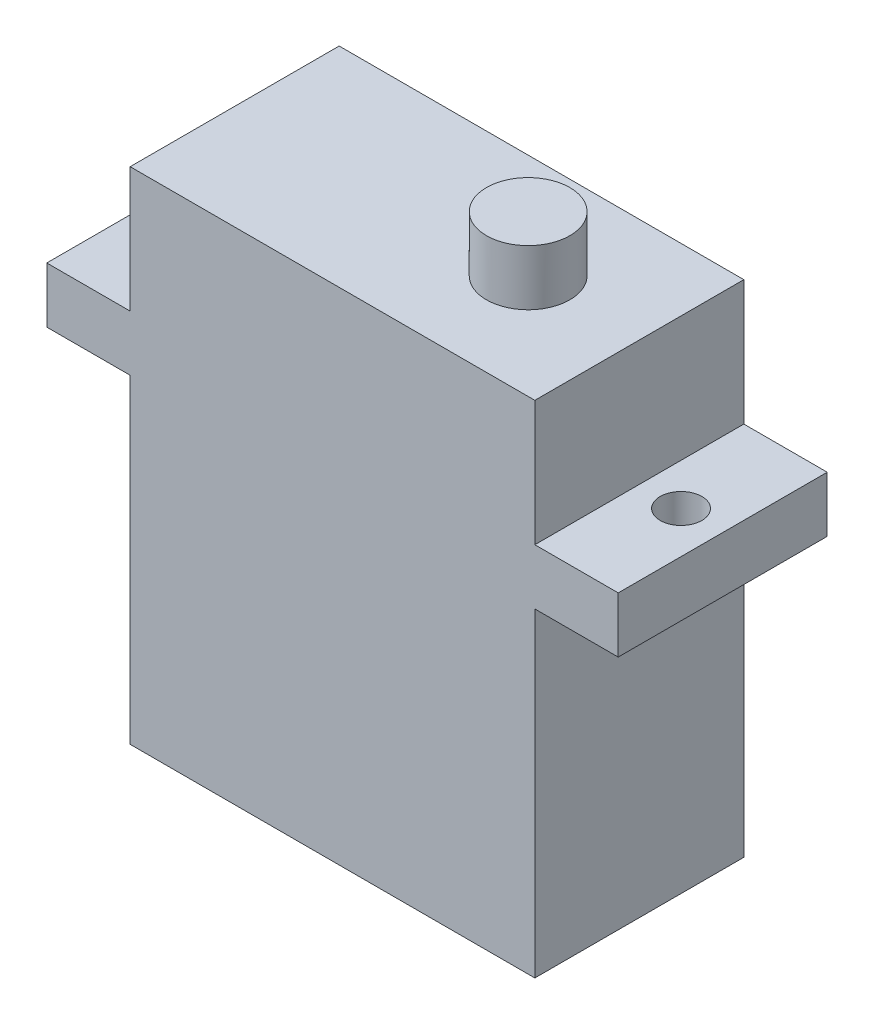
SolidWorks part; units mm, degrees
ref_plane "Front Plane" through (0, 0, 0) normal (0, 0, 1) x (1, 0, 0)
ref_plane "Top Plane" through (0, 0, 0) normal (0, 1, 0) x (1, 0, 0)
ref_plane "Right Plane" through (0, 0, 0) normal (1, 0, 0) x (0, 0, -1)
sketch "Sketch2" plane through (0, 0, 0) normal (0, 1, 0) x (1, 0, 0)
  line L1 (-11.557, 5.969) -> (11.557, 5.969)
  line L2 (-11.557, 5.969) -> (-11.557, -5.969)
  line L3 (-11.557, -5.969) -> (11.557, -5.969)
  line L4 (11.557, 5.969) -> (11.557, -5.969)
  line L5 (-11.557, 5.969) -> (11.557, -5.969) construction
  line L6 (-11.557, -5.969) -> (11.557, 5.969) construction
  point P0 (0, 0)
  dimension "D1" = 11.938
  dimension "D2" = 23.114
extrude "Boss-Extrude1" add sketch "Sketch2" along normal blind 28.575 contours L2 L1 L4 L3
sketch "Sketch3" plane through (0, 0, 5.969) normal (0, 0, 1) x (1, 0, 0)
  line L0 (11.557, 28.575) -> (11.557, 0) construction
  line L1 (11.557, 21.4313) -> (16.3195, 21.4313)
  line L2 (11.557, 21.4313) -> (11.557, 18.2562)
  line L3 (11.557, 18.2562) -> (16.3195, 18.2563)
  line L4 (16.3195, 21.4313) -> (16.3195, 18.2563)
  line L5 (-11.557, 0) -> (11.557, 0) construction
  dimension "D1" = 18.2562
  dimension "D2" = 3.175
  dimension "D3" = 4.7625
extrude "Boss-Extrude2" add sketch "Sketch3" against normal through all contours L2 L1 L4 L3
mirror "Mirror1" about plane through (0, 0, 0) normal (1, 0, 0) of "Boss-Extrude2"
sketch "Sketch5" plane through (0, 28.575, 0) normal (0, 1, 0) x (1, 0, 0)
  line L0 (11.557, 5.969) -> (11.557, -5.969) construction
  circle A0 centre (5.207, 0) radius 2.3813
  dimension "D1" = 4.7625
  dimension "D2" = 6.35
extrude "Boss-Extrude3" add sketch "Sketch5" along normal blind 3.175
sketch "Sketch8" plane through (0, 21.4313, 0) normal (0, 1, 0) x (1, 0, 0)
  line L0 (11.557, 5.969) -> (11.557, -5.969) construction
  circle A0 centre (13.9383, 0) radius 1.1906
  dimension "D2" = 2.3813
  dimension "D1" = 2.3813
extrude "Cut-Extrude1" cut sketch "Sketch8" against normal through all
mirror "Mirror2" about plane through (0, 0, 0) normal (1, 0, 0) of "Cut-Extrude1"
